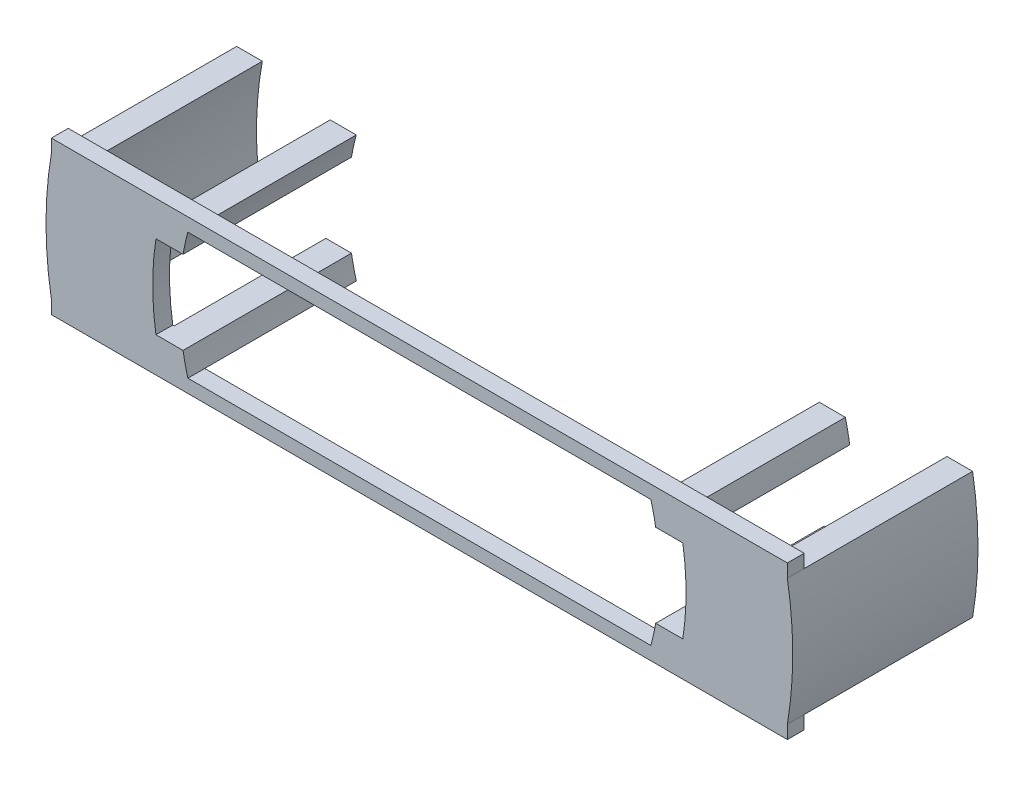
SolidWorks part; units mm, degrees
ref_plane "Front Plane" through (0, 0, 0) normal (0, 0, 1) x (1, 0, 0)
ref_plane "Top Plane" through (0, 0, 0) normal (0, 1, 0) x (1, 0, 0)
ref_plane "Right Plane" through (0, 0, 0) normal (1, 0, 0) x (0, 0, -1)
sketch "Sketch1" plane through (0, 0, 0) normal (0, 0, 1) x (1, 0, 0)
  line L0 (0, 0) -> (-40, 0) construction
  line L3 (-55.4968, -9.5352) -> (-34.9113, -9.5352)
  line L4 (55.4968, 9.5352) -> (34.9113, 9.5352)
  line L5 (34.9113, -9.5352) -> (55.4968, -9.5352)
  line L6 (-34.9113, 9.5352) -> (-55.4968, 9.5352)
  arc A4 (-34.9113, 9.5352) -> (-34.9113, -9.5352) centre (0, 0) ccw
  arc A5 (34.9113, -9.5352) -> (34.9113, 9.5352) centre (0, 0) ccw
  arc A6 (-55.4968, 9.5352) -> (-55.4968, -9.5352) centre (0, 0) ccw
  arc A7 (55.4968, -9.5352) -> (55.4968, 9.5352) centre (0, 0) ccw
extrude "Boss-Extrude1" add sketch "Sketch1" along normal blind 2.54 and the other way blind 25.4
sketch "Sketch3" plane through (0, 0, 2.54) normal (0, 0, 1) x (1, 0, 0)
  line L0 (39.7306, 6.27) -> (31.32, 6.27)
  line L1 (39.7306, -6.27) -> (31.32, -6.27)
  line L2 (-31.32, 6.27) -> (-39.7306, 6.27)
  line L3 (-31.32, -6.27) -> (-39.7306, -6.27)
  line L4 (0, 0) -> (-40.2223, 0) construction
  arc A0 (39.7306, -6.27) -> (39.7306, 6.27) centre (0, 0) ccw
  arc A1 (31.32, -6.27) -> (31.32, 6.27) centre (0, 0) ccw
  arc A2 (-31.32, 6.27) -> (-31.32, -6.27) centre (0, 0) ccw
  arc A3 (-39.7306, 6.27) -> (-39.7306, -6.27) centre (0, 0) ccw
  dimension "D1" = 6.27
extrude "Cut-Extrude1" cut sketch "Sketch3" against normal blind 38.1
sketch "Sketch5" plane through (0, 0, 0) normal (0, 0, 1) x (1, 0, 0)
  circle A0 centre (0, 0) radius 40
  circle A1 centre (0, 0) radius 52.5
extrude "Cut-Extrude2" cut sketch "Sketch5" against normal through all
sketch "Sketch6" plane through (0, -9.5352, 0) normal (0, -1, 0) x (1, 0, 0)
  line L0 (55.4968, -25.4) -> (55.4968, 2.54) construction
  line L1 (-55.4968, 2.54) -> (55.4968, 2.54)
  line L2 (-55.4968, 2.54) -> (-55.4968, 0)
  line L3 (-55.4968, 0) -> (55.4968, 0)
  line L4 (55.4968, 2.54) -> (55.4968, 0)
  line L5 (-38.8469, 0) -> (-51.6268, 0) construction
extrude "Boss-Extrude2" add sketch "Sketch6" along normal blind 2
sketch "Sketch7" plane through (0, 9.5352, 0) normal (0, 1, 0) x (1, 0, 0)
  line L0 (55.4968, 25.4) -> (55.4968, -2.54) construction
  line L1 (-55.4968, -2.54) -> (55.4968, -2.54)
  line L2 (-55.4968, -2.54) -> (-55.4968, 0)
  line L3 (-55.4968, 0) -> (55.4968, 0)
  line L4 (55.4968, -2.54) -> (55.4968, 0)
  line L5 (-51.6268, 0) -> (-38.8469, 0) construction
extrude "Boss-Extrude3" add sketch "Sketch7" along normal blind 2
sketch "Sketch8" plane through (0, 0, -25.4) normal (0, 0, -1) x (-1, 0, 0)
  line L5 (42.8065, 20.6042) -> (-42.8065, 20.6042)
  line L6 (42.8065, 20.6042) -> (42.8065, -20.6042)
  line L7 (42.8065, -20.6042) -> (-42.8065, -20.6042)
  line L8 (-42.8065, 20.6042) -> (-42.8065, -20.6042)
  line L9 (42.8065, 20.6042) -> (-42.8065, -20.6042) construction
  line L10 (42.8065, -20.6042) -> (-42.8065, 20.6042) construction
  point P0 (0, 0)
extrude "Cut-Extrude4" cut sketch "Sketch8" against normal blind 2.54
